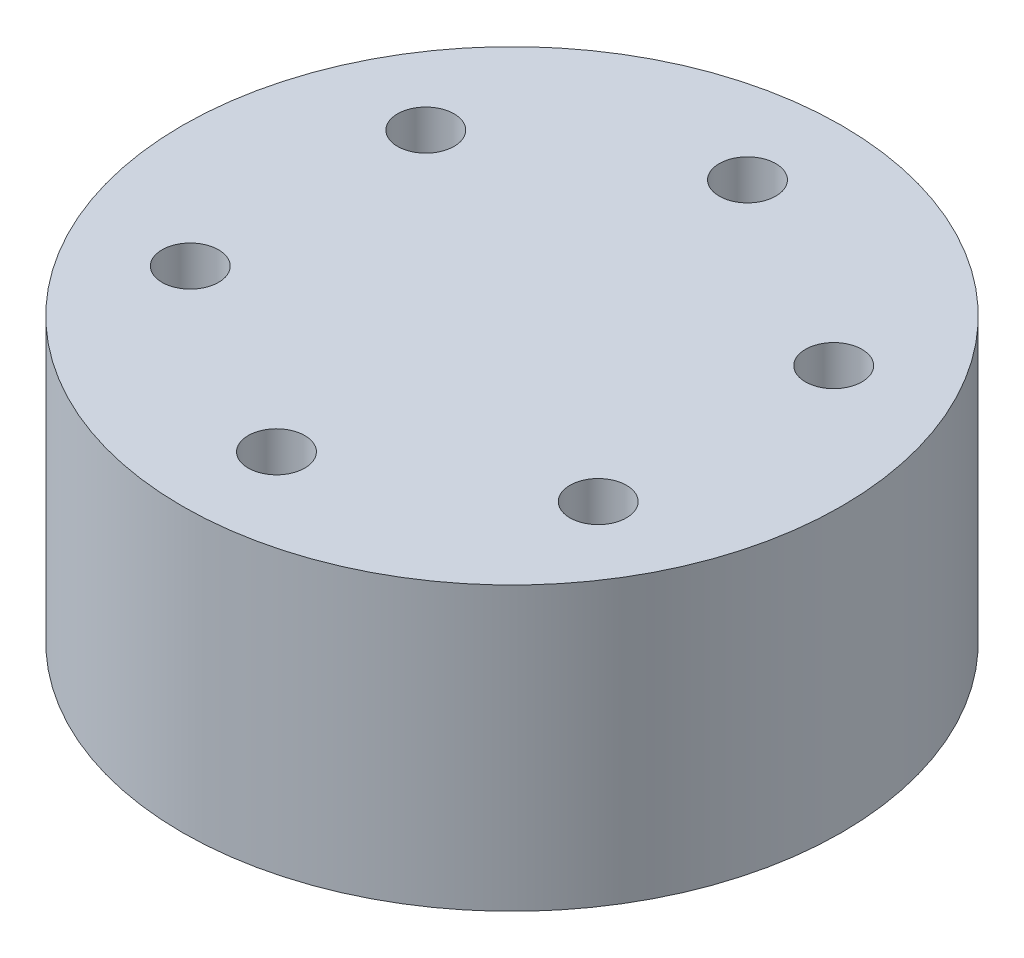
SolidWorks part; units mm, degrees
ref_plane "Спереди" through (0, 0, 0) normal (0, 0, 1) x (1, 0, 0)
ref_plane "Сверху" through (0, 0, 0) normal (0, 1, 0) x (1, 0, 0)
ref_plane "Справа" through (0, 0, 0) normal (1, 0, 0) x (0, 0, -1)
sketch "Эскиз5" plane through (0, 0, 0) normal (0, 1, 0) x (1, 0, 0)
  circle A0 centre (0, 0) radius 17.5
  dimension "D1" = 35
extrude "Бобышка-Вытянуть1" add sketch "Эскиз5" along normal blind 15
sketch "Эскиз6" plane through (0, 15, 0) normal (0, 1, 0) x (1, 0, 0)
  circle A1 centre (0, 0) radius 12.5 construction
  circle A3 centre (0, 12.5) radius 1.5
  circle A5 centre (10.8253, 6.25) radius 1.5
  circle A7 centre (10.8253, -6.25) radius 1.5
  circle A9 centre (0, -12.5) radius 1.5
  circle A11 centre (-10.8253, -6.25) radius 1.5
  circle A13 centre (-10.8253, 6.25) radius 1.5
extrude "Вырез-Вытянуть1" cut sketch "Эскиз6" against normal blind 5
